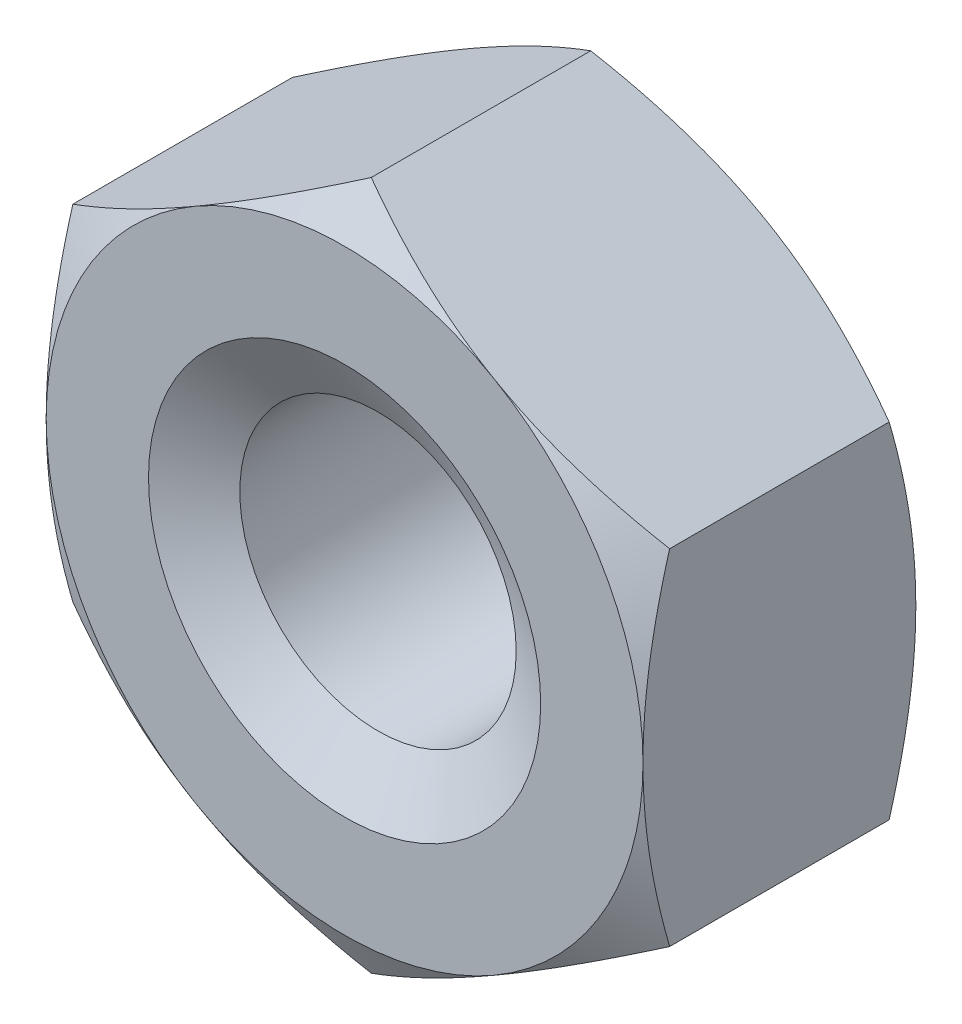
SolidWorks part; units mm, degrees
ref_plane "前视基准面" through (0, 0, 0) normal (0, 0, 1) x (1, 0, 0)
ref_plane "上视基准面" through (0, 0, 0) normal (0, 1, 0) x (1, 0, 0)
ref_plane "右视基准面" through (0, 0, 0) normal (1, 0, 0) x (0, 0, -1)
sketch "草图1" plane through (0, 0, 0) normal (1, 0, 0) x (0, 0, -1)
  line L0 (0, 3.83) -> (0, -3.83) construction
  line L1 (0, 0) -> (3.2, 0) construction
  line L2 (0, 0) -> (0, 3.83)
  line L3 (0, 3.83) -> (3.2, 3.83)
  line L4 (3.2, 3.83) -> (3.2, 0)
  line L5 (0, 2) -> (3.2, 2)
  line L6 (0, 1.6211) -> (3.2, 1.6211)
  line L7 (2.8, 3.83) -> (2.8, 0)
  line L8 (0, 3.5) -> (0.1905, 3.83)
  line L9 (0, 2) -> (0.2187, 1.6211)
  line L10 (0, -2) -> (0.2187, -1.6211)
  line L11 (2.8, 2.95) -> (3.2, 2.95)
  point P5 (0.9, 0)
  point P10 (2.5, 0)
  point P22 (0, 4.6)
  dimension "e" = 7.66
  dimension "m" = 3.2
  dimension "mw" = 2.3
  dimension "D" = 4
  dimension "P" = 0.7
  dimension "D81" = 3.2422
  dimension "c" = 0.4
  dimension "β" = 30
  dimension "s" = 7
  dimension "θ" = 120
  dimension "dw" = 5.9
  dimension "da" = 4.6
sketch "草图2" plane through (0, 0, 0) normal (0, 0, 1) x (1, 0, 0)
  line L1 (0, 4.0415) -> (-3.5, 2.0207)
  line L2 (-3.5, 2.0207) -> (-3.5, -2.0207)
  line L3 (-3.5, -2.0207) -> (0, -4.0415)
  line L4 (0, -4.0415) -> (3.5, -2.0207)
  line L5 (3.5, -2.0207) -> (3.5, 2.0207)
  line L6 (3.5, 2.0207) -> (0, 4.0415)
  circle A0 centre (0, 0) radius 3.5 construction
  circle A1 centre (0, 0) radius 1.6211
  dimension "D1" = 7
sketch "草图3" plane through (0, 0, 0) normal (0, 0, 1) x (1, 0, 0)
  line L0 (0, 4.0415) -> (-3.5, 2.0207) construction
  line L1 (3.5, 2.0207) -> (0, 4.0415) construction
  line L2 (3.5, -2.0207) -> (3.5, 2.0207) construction
  line L3 (0, -4.0415) -> (3.5, -2.0207) construction
  line L4 (-3.5, -2.0207) -> (0, -4.0415) construction
  line L5 (-3.5, 2.0207) -> (-3.5, -2.0207) construction
  line L6 (0, 4.0415) -> (-3.5, 2.0207)
  line L7 (3.5, 2.0207) -> (0, 4.0415)
  line L8 (3.5, -2.0207) -> (3.5, 2.0207)
  line L9 (0, -4.0415) -> (3.5, -2.0207)
  line L10 (-3.5, -2.0207) -> (0, -4.0415)
  line L11 (-3.5, 2.0207) -> (-3.5, -2.0207)
  circle A0 centre (0, 0) radius 1.6211 construction
  circle A1 centre (0, 0) radius 1.6211
extrude "凸台-拉伸1" add sketch "草图3" against normal up to vertex (3.2 mm away) up to point (0, 0, -3.2)
cosmetic thread "装饰螺纹线1" parameters "D2"=4
sketch "草图4" plane through (0, 0, 0) normal (1, 0, 0) x (0, 0, -1)
  line L1 (0, 2.3) -> (0.3919, 1.6211)
  line L2 (0, 0) -> (3.2, 0) construction
  line L3 (0, 0) -> (3.2, 0) construction
  line L4 (1.6, 0) -> (1.6, 3.83) construction
  line L5 (0, 3.83) -> (3.2, 3.83) construction
  line L6 (0.3919, 1.6211) -> (0.3919, 0)
  line L7 (0.3919, 0) -> (0, 0)
  line L8 (0, 0) -> (0, 2.3)
  line L9 (3.2, 0) -> (3.2, 2.3)
  line L10 (2.8081, 0) -> (3.2, 0)
  line L11 (2.8081, 1.6211) -> (2.8081, 0)
  line L12 (3.2, 2.3) -> (2.8081, 1.6211)
  line L16 (0, 2) -> (0.2187, 1.6211) construction
  line L17 (0, 1.6211) -> (3.2, 1.6211) construction
  dimension "D1" = 4.6
revolve "切除-旋转1" cut sketch "草图4" angle 360 mid plane about L3
sketch "草图5" plane through (0, 0, 0) normal (0, 0, 1) x (1, 0, 0)
  circle A0 centre (0, 0) radius 3.5
  circle A1 centre (0, 0) radius 5.745
  circle A2 centre (0, 0) radius 3.5 construction
  dimension "D1" = 11.49
extrude "切除-拉伸1" cut sketch "草图5" against normal blind 0.64 draft 60
sketch "草图7" plane through (0, 0, -3.2) normal (0, 0, -1) x (-1, 0, 0)
  circle A1 centre (0, 0) radius 5.745
  circle A2 centre (0, 0) radius 5.745
  circle A3 centre (0, 0) radius 3.5
  circle A4 centre (0, 0) radius 3.5
  dimension "D1" = 0
  dimension "D2" = 0
extrude "切除-拉伸2" cut sketch "草图7" against normal blind 0.64 draft 60
sketch "草图6" [suppressed] plane through (0, 0, 0) normal (1, 0, 0) x (0, 0, -1)
  line L0 (51, 44.1) -> (50, 44.1)
  line L1 (50, 44.1) -> (50, 54.8483)
  line L2 (50, 54.8483) -> (51, 54.8483)
  line L3 (51, 54.8483) -> (51, 44.1)
  line L4 (0, 0) -> (51, 0) construction
  line L5 (0, 0) -> (51, 0) construction
  line L6 (46.7575, 54.8483) -> (4.2425, 54.8483) construction
revolve "切除-旋转2" [suppressed] cut sketch "草图6" angle 360 mid plane about L5
